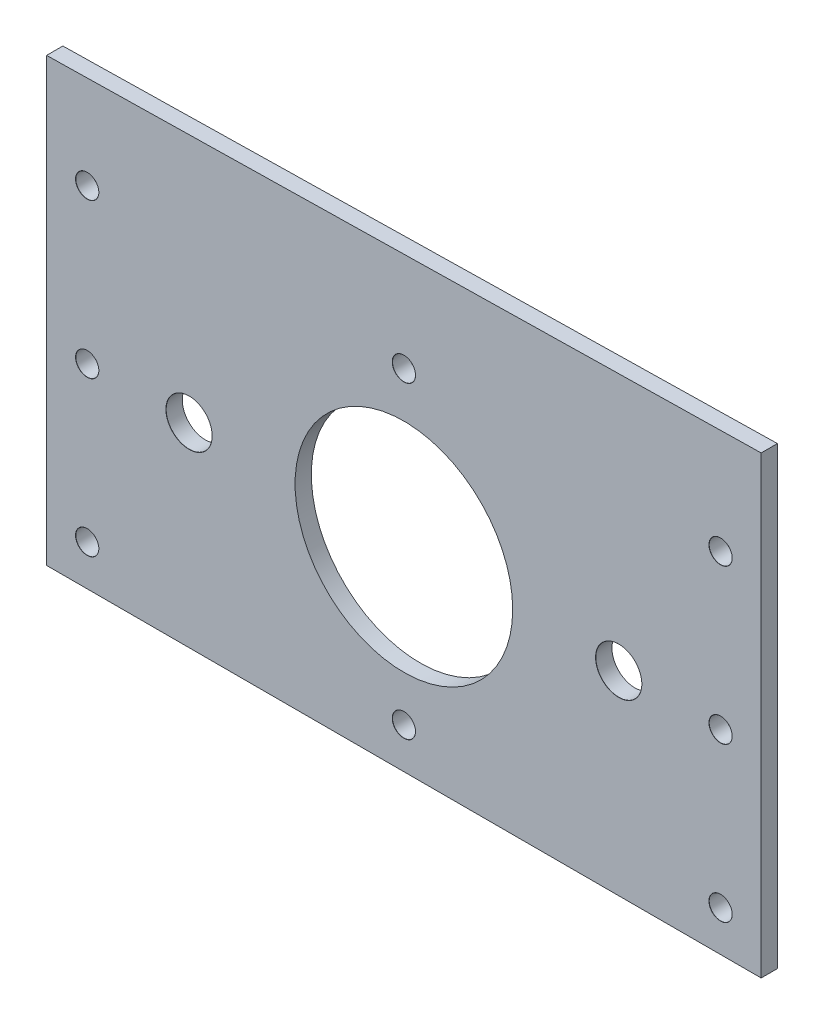
SolidWorks part; units mm, degrees
material "Alloy Steel (SS)"
ref_plane "X-Y Datum" through (0, 0, 0) normal (0, 0, 1) x (1, 0, 0)
ref_plane "X-Z Datum" through (0, 0, 0) normal (0, 1, 0) x (1, 0, 0)
ref_plane "Y-Z Datum" through (0, 0, 0) normal (1, 0, 0) x (0, 0, -1)
sketch "Sketch1" plane through (0, 0, 0) normal (0, 0, 1) x (1, 0, 0)
  line L0 (-69.85, 48.26) -> (-69.85, 38.1)
  line L1 (-69.85, 38.1) -> (69.85, 38.1) construction
  line L2 (-69.85, 38.1) -> (-69.85, -38.1)
  line L3 (-69.85, -38.1) -> (69.85, -38.1)
  line L4 (69.85, 38.1) -> (69.85, -38.1)
  line L5 (-69.85, 38.1) -> (69.85, -38.1) construction
  line L6 (-69.85, -38.1) -> (69.85, 38.1) construction
  line L7 (69.85, 38.1) -> (69.85, 50.8)
  line L10 (-69.85, 48.26) -> (69.85, 50.8)
  point P0 (0, 0)
  dimension "D1" = 139.7
  dimension "D2" = 76.2
  dimension "D3" = 12.7
  dimension "D4" = 10.16
extrude "Boss-Extrude1" add sketch "Sketch1" along normal blind 3.175
hole_wizard "M4 Clearance Hole1" positions "Sketch7" profile "Sketch8" hole size "M4" standard "ANSI Metric" end condition through all
sketch "Sketch7" plane through (0, 0, 3.175) normal (0, 0, 1) x (1, 0, 0)
  line L0 (-75.8701, 0) -> (49924.1299, 0) construction
  line L1 (0, 56.7764) -> (0, -49943.2236) construction
  line L2 (-69.85, -38.1) -> (69.85, -38.1) construction
  line L3 (-69.85, 48.26) -> (-69.85, -38.1) construction
  circle A0 centre (-61.9125, -30.1625) radius 7.9375
  circle A1 centre (-61.9125, 30.1625) radius 7.9375
  circle A2 centre (61.9125, -30.1625) radius 7.9375
  circle A3 centre (61.9125, 30.1625) radius 7.9375
  circle A4 centre (-61.9125, 0) radius 7.9375
  circle A5 centre (0, -30.1625) radius 7.9375
  circle A6 centre (61.9125, 0) radius 7.9375
  circle A7 centre (0, 30.1625) radius 7.9375
  point P0 (-61.9125, -30.1625)
  point P2 (0, -30.1625)
  point P4 (61.9125, -30.1625)
  point P6 (61.9125, 30.1625)
  point P8 (61.9125, 0)
  point P10 (0, 30.1625)
  point P12 (-61.9125, 30.1625)
  point P14 (-61.9125, 0)
  dimension "D1" = 15.875
sketch "Sketch8" plane through (-61.9125, -30.1625, 3.175) normal (1, 0, 0) x (0, -1, 0)
  line L0 (0, 0) -> (0, 3.175)
  line L1 (0, 3.175) -> (2.25, 3.175)
  line L2 (2.25, 3.175) -> (2.25, 0.025)
  line L3 (2.25, 0.025) -> (2.275, 0)
  line L5 (2.275, 0) -> (0, 0)
  line L6 (-2.25, 0.025) -> (-2.275, 0) construction
  line L11 (0, -6.35) -> (0, 107.95) construction
  dimension "Thru Hole Dia." = 4.5
  dimension "Thru Hole Depth" = 3.175
  dimension "Near C'Sink Dia." = 4.55
  dimension "Near C'Sink Angle" = 90
sketch "Sketch9" plane through (0, 0, 3.175) normal (0, 0, 1) x (1, 0, 0)
  line L0 (-42, 0) -> (42, 0) construction
  line L1 (0, -38.1) -> (0, 42.6782) construction
  line L2 (-69.85, -38.1) -> (69.85, -38.1) construction
  circle A0 centre (0, 0) radius 21.275
  circle A1 centre (42, 0) radius 4 construction
  circle A2 centre (-42, 0) radius 4 construction
  dimension "D1" = 42.55
  dimension "D3" = 8
  dimension "D2" = 42
hole_wizard "M8 Clearance Hole1" positions "Sketch10" profile "Sketch11" hole size "M8" standard "ANSI Metric" end condition through all
sketch "Sketch10" plane through (0, 0, 3.175) normal (0, 0, 1) x (1, 0, 0)
  point P0 (-42, 0)
  point P3 (42, 0)
sketch "Sketch11" plane through (-42, 0, 3.175) normal (1, 0, 0) x (0, -1, 0)
  line L0 (0, 0) -> (0, 3.175)
  line L1 (0, 3.175) -> (4.5, 3.175)
  line L2 (4.5, 3.175) -> (4.5, 0.025)
  line L3 (4.5, 0.025) -> (4.525, 0)
  line L5 (4.525, 0) -> (0, 0)
  line L6 (-4.5, 0.025) -> (-4.525, 0) construction
  line L11 (0, -6.35) -> (0, 107.95) construction
  dimension "Thru Hole Dia." = 9
  dimension "Thru Hole Depth" = 3.175
  dimension "Near C'Sink Dia." = 9.05
  dimension "Near C'Sink Angle" = 90
extrude "Center Hole" cut sketch "Sketch9" against normal through all
